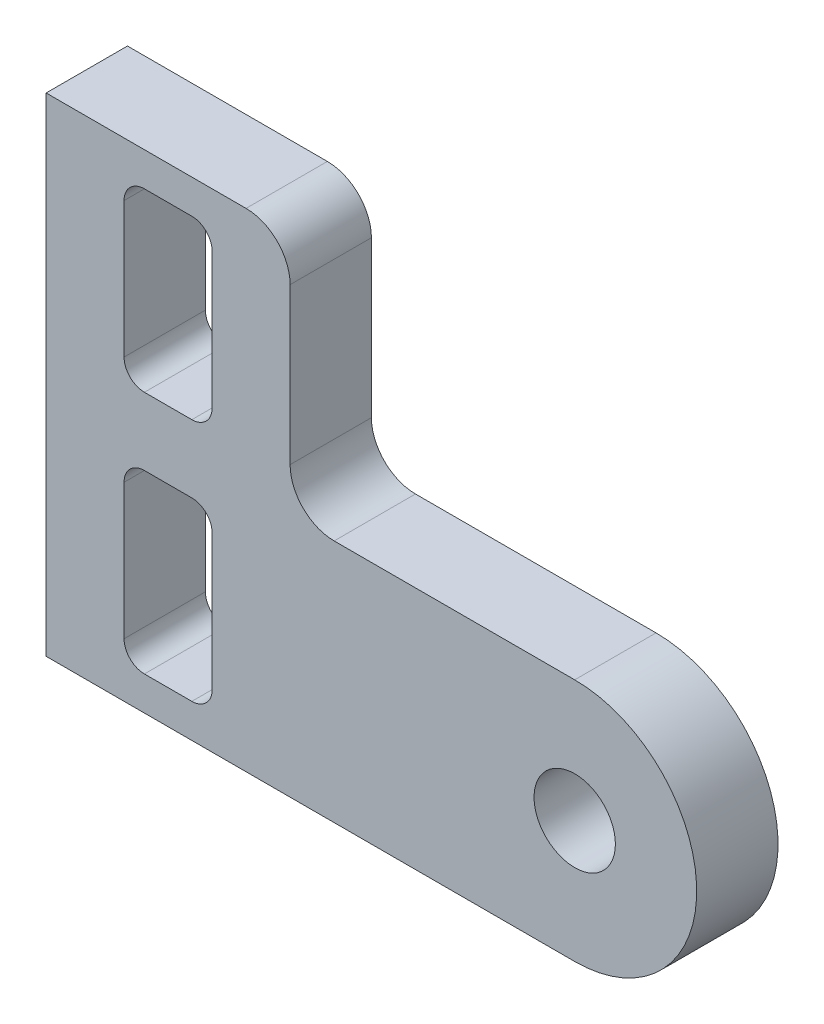
SolidWorks part; units mm, degrees
ref_plane "Alzado" through (0, 0, 0) normal (0, 0, 1) x (1, 0, 0)
ref_plane "Planta" through (0, 0, 0) normal (0, 1, 0) x (1, 0, 0)
ref_plane "Vista lateral" through (0, 0, 0) normal (1, 0, 0) x (0, 0, -1)
sketch "Model" plane through (0, 0, 0) normal (0, 0, 1) x (1, 0, 0)
  line L0 (201.0979, 264.6465) -> (181.5979, 264.6465)
  line L1 (185.2229, 265.8965) -> (186.9729, 265.8965)
  line L2 (187.7229, 266.6465) -> (187.7229, 271.6465)
  line L3 (186.9729, 272.3965) -> (185.2229, 272.3965)
  line L4 (184.4729, 271.6465) -> (184.4729, 266.6465)
  line L5 (188.9729, 282.6465) -> (181.5979, 282.6465)
  line L6 (185.2229, 274.896) -> (186.9729, 274.896)
  line L7 (187.7229, 275.646) -> (187.7229, 280.646)
  line L8 (186.9729, 281.396) -> (185.2229, 281.396)
  line L9 (184.4729, 280.646) -> (184.4729, 275.646)
  line L10 (181.5979, 282.6465) -> (181.5979, 264.6465)
  line L11 (201.0979, 273.6465) -> (192.2229, 273.6465)
  line L12 (190.5979, 281.0215) -> (190.5979, 275.2715)
  circle A0 centre (201.0979, 269.1465) radius 1.5
  arc A1 (184.4729, 266.6465) -> (185.2229, 265.8965) centre (185.2229, 266.6465) ccw
  arc A2 (186.9729, 265.8965) -> (187.7229, 266.6465) centre (186.9729, 266.6465) ccw
  arc A3 (187.7229, 271.6465) -> (186.9729, 272.3965) centre (186.9729, 271.6465) ccw
  arc A4 (185.2229, 272.3965) -> (184.4729, 271.6465) centre (185.2229, 271.6465) ccw
  arc A5 (184.4729, 275.646) -> (185.2229, 274.896) centre (185.2229, 275.646) ccw
  arc A6 (186.9729, 274.896) -> (187.7229, 275.646) centre (186.9729, 275.646) ccw
  arc A7 (187.7229, 280.646) -> (186.9729, 281.396) centre (186.9729, 280.646) ccw
  arc A8 (185.2229, 281.396) -> (184.4729, 280.646) centre (185.2229, 280.646) ccw
  arc A9 (201.0979, 264.6465) -> (201.0979, 273.6465) centre (201.0979, 269.1465) ccw
  arc A10 (190.5979, 275.2715) -> (192.2229, 273.6465) centre (192.2229, 275.2715) ccw
  arc A11 (190.5979, 281.0215) -> (188.9729, 282.6465) centre (188.9729, 281.0215) ccw
extrude "Saliente-Extruir1" add sketch "Model" along normal blind 3
